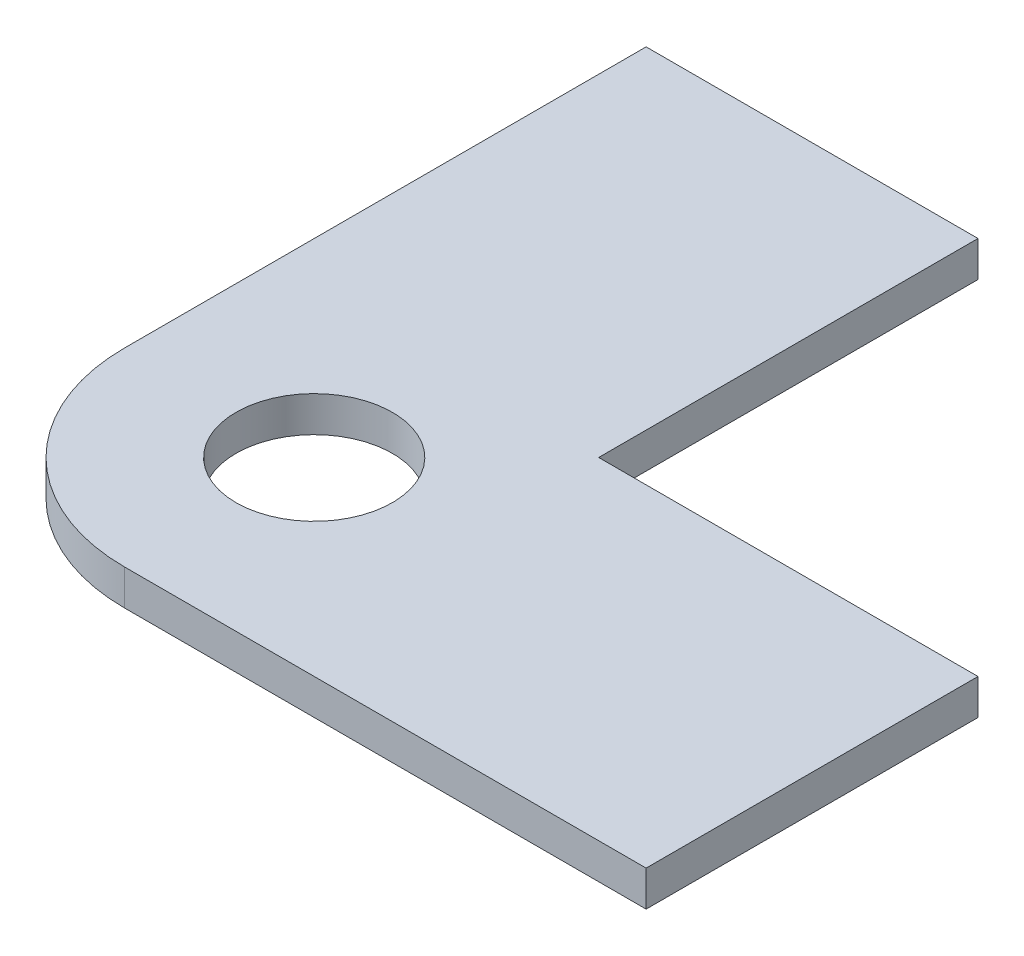
SolidWorks part; units mm, degrees
ref_plane "Front Plane" through (0, 0, 0) normal (0, 0, 1) x (1, 0, 0)
ref_plane "Top Plane" through (0, 0, 0) normal (0, 1, 0) x (1, 0, 0)
ref_plane "Right Plane" through (0, 0, 0) normal (1, 0, 0) x (0, 0, -1)
sketch "Sketch1" plane through (0, 0, 0) normal (0, 1, 0) x (1, 0, 0)
  line L0 (0, 0) -> (0, 11)
  line L1 (0, 0) -> (11, 0)
  line L2 (11, 0) -> (11, 3)
  line L3 (0, 11) -> (3, 11)
  line L4 (-3.9997, 0) -> (-3.9997, 11)
  line L5 (-3.9997, 11) -> (0, 11)
  line L6 (0, -3.9997) -> (11, -3.9997)
  line L7 (11, -3.9997) -> (11, 0)
  line L8 (3, 11) -> (3, 3)
  line L9 (3, 3) -> (11, 3)
  circle A0 centre (0, 0) radius 1.65
  arc A1 (0, -3.9997) -> (-3.9997, 0) centre (0, 0) cw
extrude "Boss-Extrude1" add sketch "Sketch1" along normal blind 0.75 contours A0 L1 L2 L9 L8 L3 L0 | A1 L6 L7 L1 A0 L0 L5 L4
